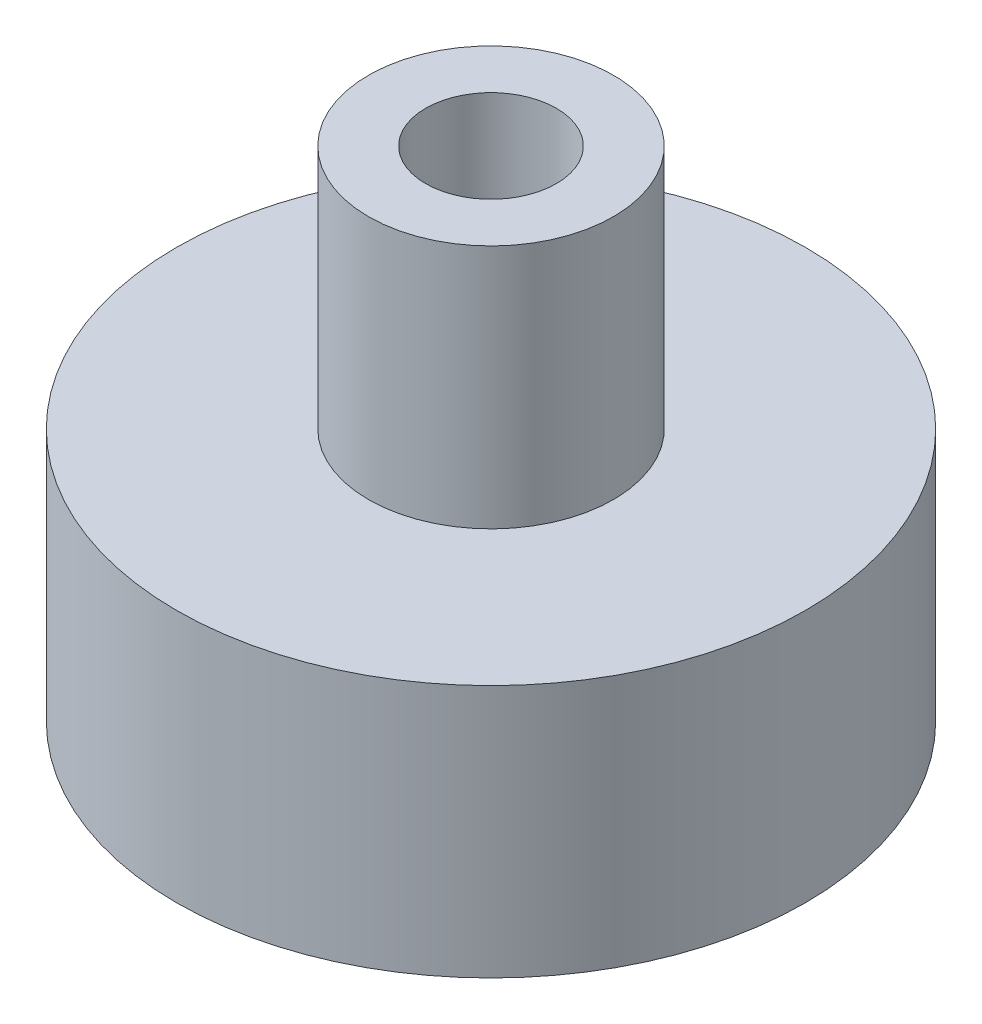
SolidWorks part; units mm, degrees
material "ABS"
ref_plane "Front Plane" through (0, 0, 0) normal (0, 0, 1) x (1, 0, 0)
ref_plane "Top Plane" through (0, 0, 0) normal (0, 1, 0) x (1, 0, 0)
ref_plane "Right Plane" through (0, 0, 0) normal (1, 0, 0) x (0, 0, -1)
sketch "Sketch1" plane through (0, 0, 0) normal (0, 1, 0) x (1, 0, 0)
  circle A0 centre (0, 0) radius 3.85
  dimension "D1" = 7.7
extrude "Boss-Extrude1" add sketch "Sketch1" along normal blind 3.1
ref_point "Point1"
sketch "Sketch2" plane through (0, 3.1, 0) normal (0, 1, 0) x (1, 0, 0)
  circle A0 centre (0, 0) radius 1.5
  circle A1 centre (0, 0) radius 0.8
  dimension "D1" = 3
  dimension "D2" = 0.7
extrude "Boss-Extrude2" add sketch "Sketch2" along normal blind 3
sketch "Sketch3" plane through (0, 3.1, 0) normal (0, 1, 0) x (1, 0, 0)
  circle A1 centre (0, 0) radius 0.8
  circle A4 centre (0, 0) radius 0.8
  dimension "D1" = 0
extrude "Cut-Extrude1" cut sketch "Sketch3" against normal through all both and the other way through all
sketch "Sketch4" plane through (0, 0, 0) normal (0, -1, 0) x (1, 0, 0)
  circle A0 centre (0, 0) radius 2.65
  circle A1 centre (0, 0) radius 3.85 construction
  dimension "D1" = 1.2
extrude "Cut-Extrude2" cut sketch "Sketch4" against normal blind 2.2
